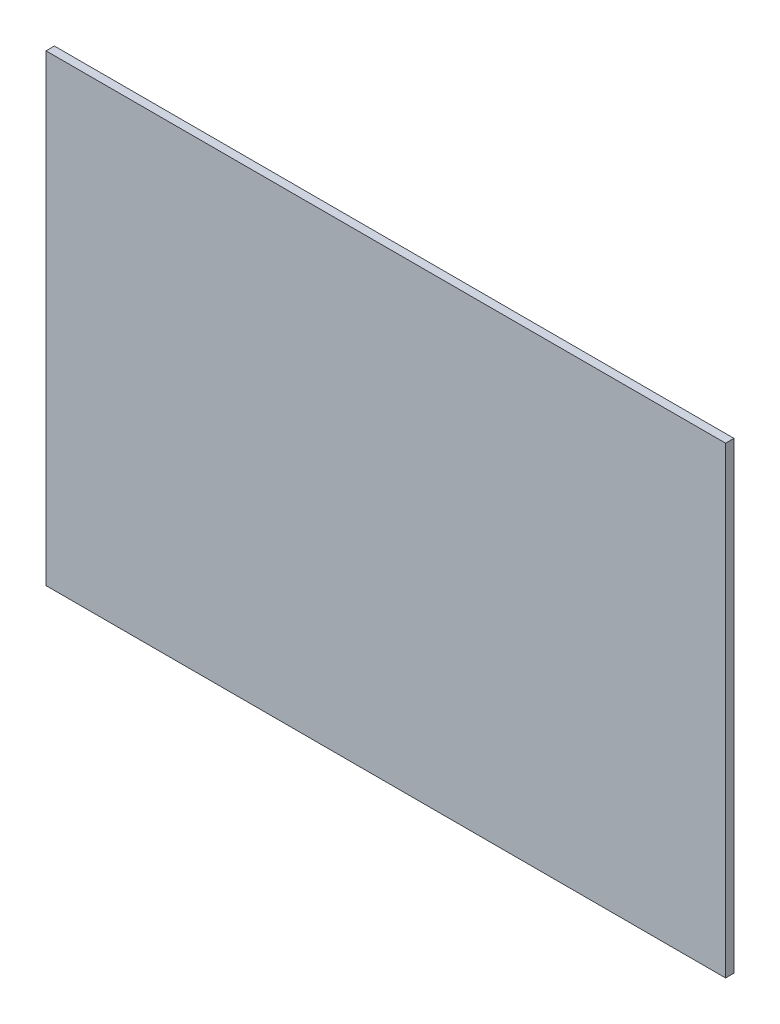
SolidWorks part; units mm, degrees
ref_plane "Front Plane" through (0, 0, 0) normal (0, 0, 1) x (1, 0, 0)
ref_plane "Top Plane" through (0, 0, 0) normal (0, 1, 0) x (1, 0, 0)
ref_plane "Right Plane" through (0, 0, 0) normal (1, 0, 0) x (0, 0, -1)
sketch "Sketch1" plane through (0, 0, 0) normal (0, 0, 1) x (1, 0, 0)
  line L2 (-39.9618, 8.0008) -> (-39.9618, -36.2996)
  line L3 (-39.9618, -36.2996) -> (25.0382, -36.2996)
  line L4 (25.0382, 8.0008) -> (25.0382, -36.2996)
  line L14 (25.0382, 8.0008) -> (-39.9618, 8.0008)
  point P0 (-39.9618, -36.2996)
  dimension "D1" = 65
extrude "Boss-Extrude1" add sketch "Sketch1" along normal blind 0.8
